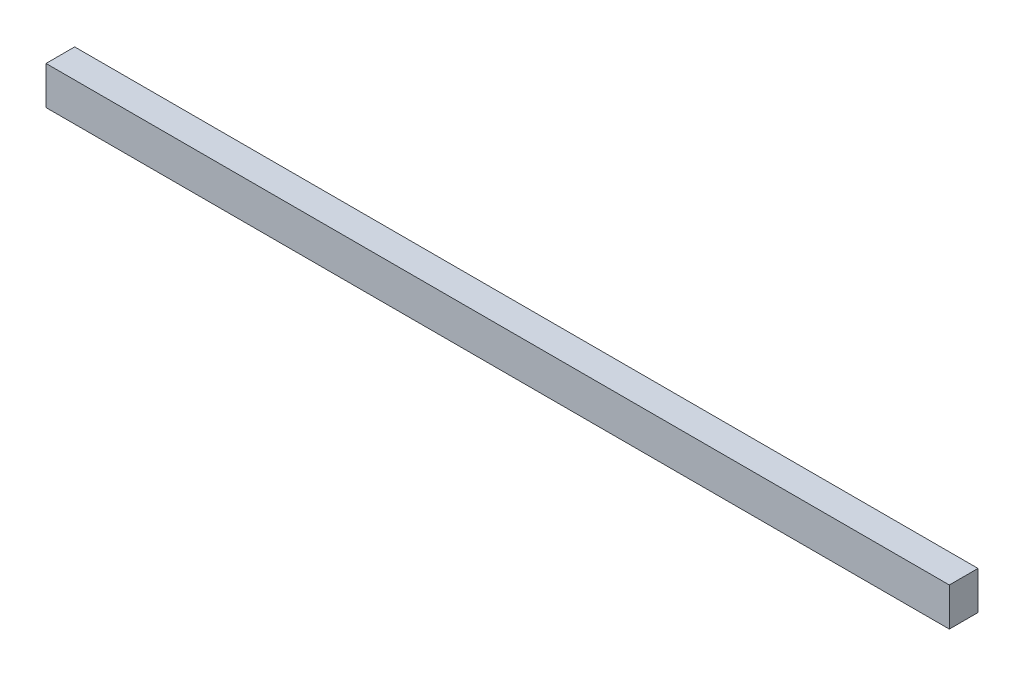
SolidWorks part; units mm, degrees
ref_plane "Front Plane" through (0, 0, 0) normal (0, 0, 1) x (1, 0, 0)
ref_plane "Top Plane" through (0, 0, 0) normal (0, 1, 0) x (1, 0, 0)
ref_plane "Right Plane" through (0, 0, 0) normal (1, 0, 0) x (0, 0, -1)
sketch "Sketch1" plane through (0, 0, 0) normal (0, 0, 1) x (1, 0, 0)
  line L1 (-1200.15, -50.8) -> (1200.15, -50.8)
  line L2 (-1200.15, -50.8) -> (-1200.15, 50.8)
  line L3 (-1200.15, 50.8) -> (1200.15, 50.8)
  line L4 (1200.15, -50.8) -> (1200.15, 50.8)
  line L5 (-1200.15, -50.8) -> (1200.15, 50.8) construction
  line L6 (-1200.15, 50.8) -> (1200.15, -50.8) construction
  point P0 (0, 0)
  dimension "D1" = 2400.3
  dimension "D2" = 101.6
extrude "Boss-Extrude1" add sketch "Sketch1" along normal mid plane 76.2
